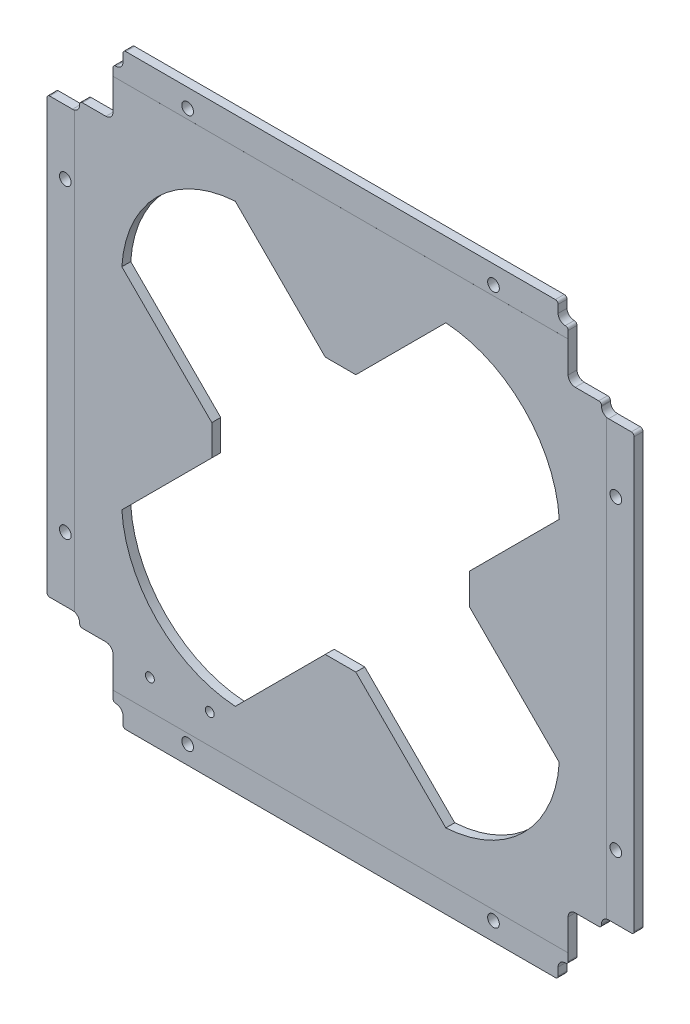
SolidWorks part; units mm, degrees
material "FR4_stuffedProtoboard"
ref_plane "Front Plane" through (0, 0, 0) normal (0, 0, 1) x (1, 0, 0)
ref_plane "Top Plane" through (0, 0, 0) normal (0, 1, 0) x (1, 0, 0)
ref_plane "Right Plane" through (0, 0, 0) normal (1, 0, 0) x (0, 0, -1)
sketch "Sketch1" plane through (0, 0, 0) normal (0, 0, 1) x (1, 0, 0)
  line L0 (53, 53) -> (-53, -53) construction
  line L1 (53, 53) -> (-53, 53)
  line L2 (53, 53) -> (53, -53)
  line L3 (53, -53) -> (-53, -53)
  line L4 (-53, 53) -> (-53, -53)
  point P4 (0, 0)
  dimension "D1" = 106
  dimension "D2" = 106
extrude "mainOutline" add sketch "Sketch1" along normal blind 1.6
sketch "axisLabels" plane through (0, 0, 0) normal (0, 0, -1) x (-1, 0, 0)
  text T0 "+Y"
  text T1 "+X"
sketch "Sketch4" plane through (0, 0, 0) normal (0, 0, -1) x (-1, 0, 0)
  line L10 (-53, 53) -> (53, 53) construction
  line L29 (41.3, 53) -> (41.3, 41.3)
  line L31 (53, 41.3) -> (41.3, 41.3)
  line L46 (53, 53) -> (53, -53) construction
  line L51 (53, 41.3) -> (53, 53)
  line L52 (53, 53) -> (41.3, 53)
  dimension "D11" = 11.7
  dimension "D12" = 11.7
extrude "railCutouts" cut sketch "Sketch4" against normal through all
sketch "Sketch13" plane through (0, 0, 0) normal (0, 0, -1) x (-1, 0, 0)
  line L0 (47.3, 39.4) -> (47.3, 41.3)
  line L2 (53, 41.3) -> (53, 39.4)
  line L5 (41.3, 53) -> (39.5, 53)
  line L6 (41.3, 53) -> (41.3, 50)
  line L7 (41.3, 50) -> (39.5, 50)
  line L8 (39.5, 53) -> (39.5, 50)
  line L9 (53, 41.3) -> (53, -53) construction
  line L10 (53, 41.3) -> (47.3, 41.3)
  line L12 (53, 39.4) -> (47.3, 39.4)
  line L13 (41.3, 41.3) -> (53, 41.3) construction
  dimension "D1" = 5.7
  dimension "D3" = 1.9
  dimension "D5" = 1.8
  dimension "D6" = 3
extrude "filletCutouts" cut sketch "Sketch13" against normal through all both and the other way through all
sketch "Sketch5" plane through (0, 0, 0) normal (0, 0, -1) x (-1, 0, 0)
  line L23 (42.198, 42.198) -> (45.4803, 45.4803) construction
  line L24 (41.3, 43.0961) -> (44.5823, 46.3784)
  line L25 (43.0961, 41.3) -> (46.3784, 44.5823)
  line L41 (41.3, 50) -> (41.3, 41.3) construction
  arc A14 (41.3, 43.0961) -> (43.0961, 41.3) centre (42.198, 42.198) ccw
  arc A15 (46.3784, 44.5823) -> (44.5823, 46.3784) centre (45.4803, 45.4803) ccw
  point P0 (41.3, 41.3)
  point P52 (43.8392, 43.8392)
  dimension "D14" = 1.27
  dimension "D7" = 45
extrude "dogbone" [suppressed] cut sketch "Sketch5" against normal through all
sketch "Sketch14" plane through (0, 0, 1.6) normal (0, 0, 1) x (1, 0, 0)
  point P1 (-47.3, 39.4)
sketch "Sketch27" plane through (0, 0, 1.6) normal (0, 0, 1) x (1, 0, 0)
  line L0 (-40.928, 42.198) -> (-40.928, 49.628)
  line L1 (-48.198, 39.028) -> (-53, 39.028)
  line L2 (-53, 39.4) -> (-53, -53) construction
  line L3 (-53, 39.028) -> (-53, 53)
  line L4 (-53, 53) -> (-39.128, 53)
  line L5 (-39.128, 53) -> (-39.128, 50.898)
  line L6 (-40.928, 49.628) -> (-40.398, 49.628)
  line L7 (-42.198, 40.928) -> (-46.928, 40.928)
  line L8 (-46.928, 40.928) -> (-46.928, 40.298)
  line L10 (53, 53) -> (-39.5, 53) construction
  arc A0 (-42.198, 40.928) -> (-40.928, 42.198) centre (-42.198, 42.198) ccw
  arc A1 (-40.398, 49.628) -> (-39.128, 50.898) centre (-40.398, 50.898) ccw
  arc A2 (-48.198, 39.028) -> (-46.928, 40.298) centre (-48.198, 40.298) ccw
  dimension "D1" = 1.27
extrude "smoothCorner" cut sketch "Sketch27" against normal blind 10
pattern_sketch "Sketch-Pattern1" [suppressed]
mirror "Mirror1" about plane through (0, 0, 0) normal (1, 0, 0) of "smoothCorner", "filletCutouts", "railCutouts"
mirror "Mirror2" about plane through (0, 0, 0) normal (0, 1, 0) of "Mirror1", "smoothCorner"
fillet "Fillet1" [suppressed] radius 0.5
fillet "Fillet10" radius 0.5 8 edges at (46.928, -40.928, 0.8) (40.928, -49.628, 0.8) (40.928, 49.628, 0.8) (46.928, 40.928, 0.8) (-46.928, 40.928, 0.8) (-40.928, 49.628, 0.8) (-46.928, -40.928, 0.8) (-40.928, -49.628, 0.8)
hole_wizard "M2 Clearance Hole1" positions "Sketch8" profile "Sketch9" hole size "M2" standard "ANSI Metric" end condition through all
sketch "Sketch8" plane through (0, 0, 0) normal (0, 0, -1) x (-1, 0, 0)
  line L0 (53, 39.028) -> (53, -39.028) construction
  line L1 (39.128, -53) -> (-39.128, -53) construction
  line L2 (-53, -39.028) -> (-53, 39.028) construction
  line L3 (53, 0) -> (-53, 0) construction
  line L5 (0, -53) -> (0, -11.6379) construction
  line L6 (53, 39.028) -> (53, -39.028) construction
  point P0 (49.5, -27.5)
  point P1 (27.5, -49.5)
  point P5 (-49.5, -27.5)
  point P30 (-27.5, -49.5)
  point P31 (-27.5, 49.5)
  point P32 (-49.5, 27.5)
  point P33 (27.5, 49.5)
  point P34 (49.5, 27.5)
  dimension "D1" = 3.5
  dimension "D2" = 3.5
  dimension "D3" = 55
  dimension "D4" = 3.5
  dimension "D5" = 55
  dimension "D6" = 55
sketch "Sketch9" plane through (-49.5, -27.5, 0) normal (1, 0, 0) x (0, 1, 0)
  line L0 (0, 0) -> (0, 1.6)
  line L1 (0, 1.6) -> (1.05, 1.6)
  line L2 (1.05, 1.6) -> (1.05, 0)
  line L5 (1.05, 0) -> (0, 0)
  line L11 (0, -6.35) -> (0, 107.95) construction
  dimension "Thru Hole Dia." = 2.1
  dimension "Thru Hole Depth" = 1.6
sketch "Sketch15" plane through (0, 0, 0) normal (0, 0, -1) x (-1, 0, 0)
  line L0 (-39.128, 53) -> (39.128, 53) construction
  line L1 (45, 53) -> (-45, 53)
  line L2 (45, 53) -> (45, 47.8)
  line L3 (45, 47.8) -> (-45, 47.8)
  line L4 (-45, 53) -> (-45, 47.8)
  line L5 (45, -53) -> (-45, -53)
  line L6 (45, -53) -> (45, -47.8)
  line L7 (45, -47.8) -> (-45, -47.8)
  line L8 (-45, -53) -> (-45, -47.8)
  line L9 (39.128, -53) -> (-39.128, -53) construction
  line L10 (-53, -39.028) -> (-53, 39.028) construction
  line L11 (-53, 45) -> (-47.8, 45)
  line L12 (-53, 45) -> (-53, -45)
  line L13 (-53, -45) -> (-47.8, -45)
  line L14 (-47.8, 45) -> (-47.8, -45)
  line L15 (53, 45) -> (47.8, 45)
  line L16 (53, 45) -> (53, -45)
  line L17 (53, -45) -> (47.8, -45)
  line L18 (47.8, 45) -> (47.8, -45)
  line L19 (53, 39.028) -> (53, -39.028) construction
  point P8 (0, 53)
  point P11 (0, -53)
  point P22 (-53, 0)
  point P25 (53, 0)
  dimension "D1" = 90
  dimension "D3" = 5.2
  dimension "D5" = 5.2
extrude "Cut-Extrude5" [suppressed] cut sketch "Sketch15" against normal blind 0.001
sketch "Sketch11" [suppressed] plane through (0, 0, 0) normal (0, 0, -1) x (-1, 0, 0)
  circle A0 centre (0, 0) radius 36
  dimension "D1" = 72
extrude "Cut-Extrude2" [suppressed] cut sketch "Sketch11" against normal through all both and the other way through all
sketch "Sketch28" [suppressed] plane through (0, 0, 0) normal (0, 0, -1) x (-1, 0, 0)
  line L0 (-12.3744, 12.3744) -> (-46.3155, -21.5668)
  line L1 (-12.3744, 12.3744) -> (12.3744, -12.3744)
  line L2 (-46.3155, -21.5668) -> (-21.5668, -46.3155)
  line L3 (12.3744, -12.3744) -> (-21.5668, -46.3155)
  line L4 (-47.8, -39.092) -> (-47.8, 39.092) construction
  dimension "D1" = 35
  dimension "D2" = 48
  dimension "D3" = 315
extrude "Cut-Extrude7" [suppressed] cut sketch "Sketch28" against normal blind 10
fillet "Fillet11" [suppressed] radius 2
sketch "Sketch16" plane through (0, 0, 1.6) normal (0, 0, 1) x (1, 0, 0)
  line L0 (-39.128, -53) -> (39.128, -53) construction
  line L1 (39.128, 53) -> (-39.128, 53) construction
  line L8 (-45, -53) -> (45, -53)
  line L9 (45, -53) -> (45, -47.8)
  line L10 (45, -47.8) -> (-45, -47.8)
  line L11 (-45, -47.8) -> (-45, -53)
  line L16 (45, 53) -> (-45, 53)
  line L17 (45, 47.8) -> (45, 53)
  line L18 (-45, 47.8) -> (45, 47.8)
  line L19 (-45, 53) -> (-45, 47.8)
  line L20 (-47.8, 45) -> (-53, 45)
  line L21 (-53, 45) -> (-53, -45)
  line L22 (-53, -45) -> (-47.8, -45)
  line L23 (-47.8, -45) -> (-47.8, 45)
  line L24 (-47.8, 45) -> (-53, 45)
  line L25 (-53, 45) -> (-53, -45)
  line L26 (-53, -45) -> (-47.8, -45)
  line L27 (-47.8, -45) -> (-47.8, 45)
  line L28 (53, 45) -> (47.8, 45)
  line L29 (47.8, 45) -> (47.8, -45)
  line L30 (47.8, -45) -> (53, -45)
  line L31 (53, -45) -> (53, 45)
  line L32 (53, 45) -> (47.8, 45)
  line L33 (47.8, 45) -> (47.8, -45)
  line L34 (47.8, -45) -> (53, -45)
  line L35 (53, -45) -> (53, 45)
  dimension "D1" = 5.2
  dimension "D3" = 0
  dimension "D4" = 0
extrude "Cut-Extrude6" cut sketch "Sketch16" against normal blind 0.001
sketch "Sketch30" plane through (0, 0, 0) normal (0, 0, -1) x (-1, 0, 0)
  line L0 (-18.93, -39.33) -> (-2.75, -23.15)
  line L1 (-2.75, -23.15) -> (2.75, -23.15)
  line L2 (2.75, -23.15) -> (18.93, -39.33)
  line L3 (-39.33, -18.93) -> (-23.15, -2.75)
  line L4 (-23.15, -2.75) -> (-23.15, 2.75)
  line L5 (-23.15, 2.75) -> (-39.33, 18.93)
  line L6 (-18.93, 39.33) -> (-2.75, 23.15)
  line L7 (-2.75, 23.15) -> (2.75, 23.15)
  line L8 (2.75, 23.15) -> (18.93, 39.33)
  line L9 (39.33, -18.93) -> (23.15, -2.75)
  line L10 (23.15, -2.75) -> (23.15, 2.75)
  line L11 (23.15, 2.75) -> (39.33, 18.93)
  line L12 (0, -23.15) -> (0, 23.15) construction
  line L13 (-23.15, 0) -> (23.15, 0) construction
  arc A0 (-18.93, -39.33) -> (-39.33, -18.93) centre (-17.5661, -17.5661) cw
  arc A1 (-39.33, 18.93) -> (-18.93, 39.33) centre (-17.5661, 17.5661) cw
  arc A2 (18.93, 39.33) -> (39.33, 18.93) centre (17.5661, 17.5661) cw
  arc A3 (39.33, -18.93) -> (18.93, -39.33) centre (17.5661, -17.5661) cw
  dimension "D5" = 21.8066
  dimension "D1" = 135
  dimension "D2" = 28.85
  dimension "D3" = 22.882
  dimension "D4" = 5.5
extrude "Cut-Extrude8" cut sketch "Sketch30" against normal blind 10
sketch "Sketch29" plane through (0, 0, 0) normal (0, 0, -1) x (-1, 0, 0)
  circle A0 centre (34.285, -42.5) radius 0.8
  circle A1 centre (23.515, -42.5) radius 0.8
  circle A2 centre (49.5, -27.5) radius 1.05 construction
  circle A4 centre (27.5, -49.5) radius 1.05 construction
  dimension "D1" = 1.6
  dimension "D2" = 10.77
  dimension "D3" = 7
  dimension "D4" = 25.985
extrude "Connector Location" cut sketch "Sketch29" against normal blind 10
sketch "Sketch31" plane through (0, 0, 0) normal (0, 0, -1) x (-1, 0, 0)
  line L1 (52.8, -52.8) -> (-52.8, -52.8)
  line L2 (52.8, -52.8) -> (52.8, 52.8)
  line L3 (52.8, 52.8) -> (-52.8, 52.8)
  line L4 (-52.8, -52.8) -> (-52.8, 52.8)
  circle A0 centre (27.5, -49.5) radius 1.05 construction
  circle A1 centre (49.5, -27.5) radius 1.05 construction
  circle A2 centre (-27.5, 49.5) radius 1.05 construction
  circle A5 centre (-49.5, 27.5) radius 1.05 construction
  dimension "D2" = 3.3
  dimension "D4" = 3.3
  dimension "D1" = 3.3
  dimension "D3" = 3.3
extrude "Cut-Extrude-Thin1" cut sketch "Sketch31" against normal through all both and the other way through all thin thin type one direction wall 10
fillet "Fillet12" radius 0.5 8 edges at (-52.8, 39.028, 0.7995) (-39.128, 52.8, 0.7995) (39.128, 52.8, 0.7995) (52.8, 39.028, 0.7995) (52.8, -39.028, 0.7995) (39.128, -52.8, 0.7995) (-39.128, -52.8, 0.7995) (-52.8, -39.028, 0.7995)
equation "\"ConnectorSideDistance\"= 25.985"
equation "\"ConnectorTopDistance\"= 7"
equation "\"D3@Sketch29\"=\"ConnectorTopDistance\""
equation "\"D4@Sketch29\"=\"ConnectorSideDistance\""
